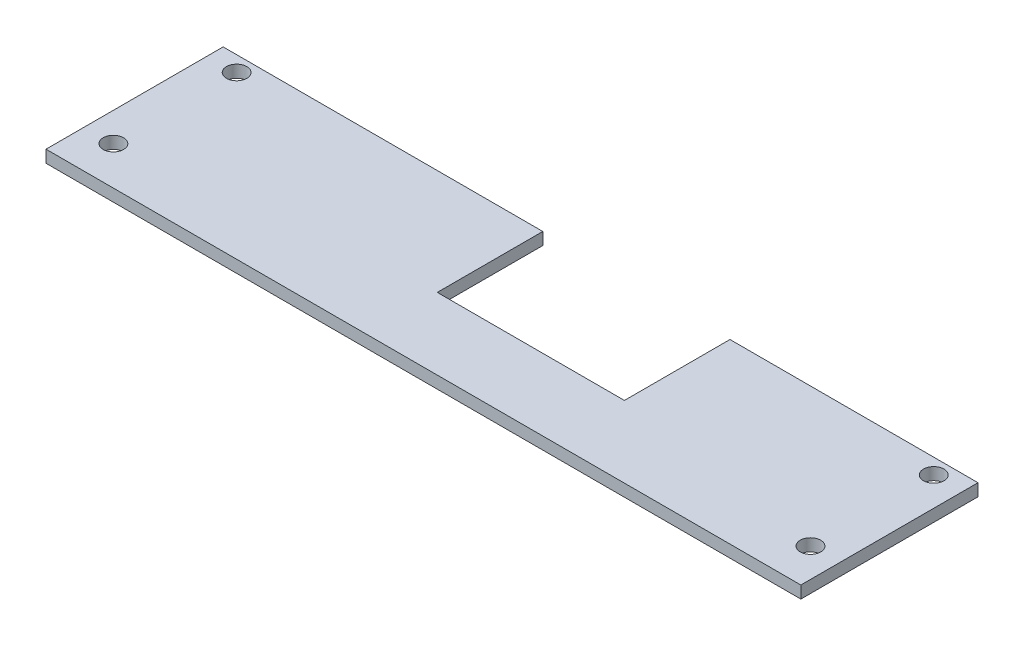
SolidWorks part; units mm, degrees
ref_plane "Front Plane" through (0, 0, 0) normal (0, 0, 1) x (1, 0, 0)
ref_plane "Top Plane" through (0, 0, 0) normal (0, 1, 0) x (1, 0, 0)
ref_plane "Right Plane" through (0, 0, 0) normal (1, 0, 0) x (0, 0, -1)
sketch "Sketch1" plane through (0, 0, 0) normal (0, 1, 0) x (1, 0, 0)
  line L1 (0, 0) -> (196, 0)
  line L2 (0, 0) -> (0, 46)
  line L3 (0, 46) -> (196, 46)
  line L4 (196, 0) -> (196, 46)
  dimension "D1" = 46
  dimension "D2" = 196
extrude "Boss-Extrude1" add sketch "Sketch1" along normal blind 3.175
sketch "Sketch2" plane through (0, 3.175, 0) normal (0, 1, 0) x (1, 0, 0)
  line L0 (113, 35.9819) -> (83, 35.9819) construction
  line L1 (196, 46) -> (0, 46) construction
  line L2 (98, 46) -> (98, 20.9819) construction
  line L8 (83, 35.9819) -> (83, 46)
  line L9 (83, 46) -> (113, 46)
  line L10 (113, 46) -> (113, 35.9819)
  line L12 (83, 46) -> (131.596, 46)
  line L13 (83, 46) -> (83, 18.5969)
  line L14 (83, 18.5969) -> (131.596, 18.5969)
  line L15 (131.596, 46) -> (131.596, 18.5969)
  arc A6 (83, 35.9819) -> (113, 35.9819) centre (98, 35.9819) ccw
  point P15 (98, 35.9819)
  dimension "D1" = 30
extrude "Cut-Extrude1" cut sketch "Sketch2" against normal blind 3.175
sketch "Sketch3" plane through (0, 3.175, 0) normal (0, 1, 0) x (1, 0, 0)
  line L0 (196, 0) -> (196, 46) construction
  line L1 (7.5, 36) -> (188.5, 36) construction
  line L2 (7.5, 36) -> (7.5, 10) construction
  line L3 (7.5, 10) -> (188.5, 10) construction
  line L4 (188.5, 36) -> (188.5, 10) construction
  line L5 (7.5, 36) -> (188.5, 10) construction
  line L6 (7.5, 10) -> (188.5, 36) construction
  line L7 (0, 0) -> (196, 0) construction
  line L8 (188.5, 36) -> (188.5, 42)
  line L10 (7.5, 36) -> (7.5, 42)
  line L11 (98, 46) -> (98, 0) construction
  line L14 (0, 23) -> (196, 23) construction
  line L15 (0, 46) -> (0, 0) construction
  line L16 (83, 46) -> (0, 46) construction
  line L17 (196, 46) -> (131.596, 46) construction
  point P1 (188.5, 10)
  point P2 (7.5, 36)
  point P3 (7.5, 10)
  point P13 (188.5, 42)
  point P18 (7.5, 42)
  point P31 (98, 23)
  point P32 (0, 0)
  point P35 (0, 0)
  dimension "D1" = 7.5
  dimension "D2" = 10
  dimension "D3" = 6
  dimension "D4" = 6
  dimension "D5" = 181
  dimension "D6" = 4
hole_wizard "M5 Clearance Hole1" positions "Sketch3" profile "Sketch4" hole size "M5" standard "ANSI Metric"
sketch "Sketch4" plane through (188.5, 3.175, -10) normal (1, 0, 0) x (0, 0, 1)
  line L0 (0, 0) -> (0, 3.175)
  line L1 (0, 3.175) -> (2.65, 3.175)
  line L2 (2.65, 3.175) -> (2.65, 0)
  line L5 (2.65, 0) -> (0, 0)
  line L11 (0, -6.35) -> (0, 107.95) construction
  dimension "Thru Hole Dia." = 5.3
  dimension "Thru Hole Depth" = 3.175
